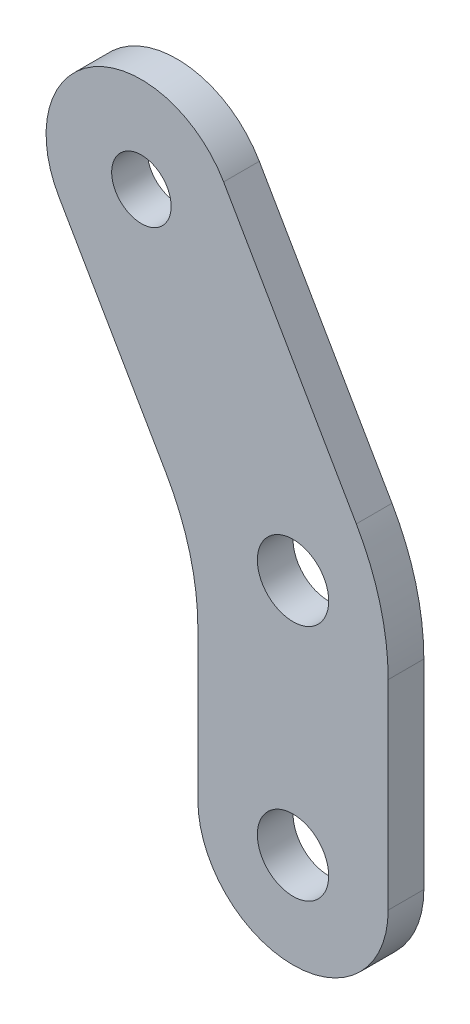
SolidWorks part; units mm, degrees
material "5052-H32"
ref_plane "Front Plane" through (0, 0, 0) normal (0, 0, 1) x (1, 0, 0)
ref_plane "Top Plane" through (0, 0, 0) normal (0, 1, 0) x (1, 0, 0)
ref_plane "Right Plane" through (0, 0, 0) normal (1, 0, 0) x (0, 0, -1)
sketch "Sketch1" plane through (0, 0, 0) normal (0, 0, 1) x (1, 0, 0)
  line L0 (-8, 0) -> (-8, 17.8564)
  line L1 (-8, 17.8564) -> (-19.6922, 38.108)
  line L2 (-19.6922, 38.108) -> (-5.8358, 46.108) construction
  line L3 (-5.8358, 46.108) -> (8, 22.1436)
  line L4 (8, 0) -> (8, 22.1436)
  line L5 (0, 0) -> (0, 20) construction
  line L6 (-8, 17.8564) -> (8, 17.8564) construction
  line L7 (0, 20) -> (-12.764, 42.108) construction
  circle A0 centre (0, 0) radius 3
  arc A1 (-8, 0) -> (8, 0) centre (0, 0) ccw
  arc A2 (-5.8358, 46.108) -> (-19.6922, 38.108) centre (-12.764, 42.108) ccw
  circle A4 centre (0, 20) radius 3
  circle A5 centre (0, 0) radius 44 construction
  circle A6 centre (-12.7498, 42.1123) radius 2.5
  point P16 (-12.5, 41.6506)
  point P17 (-11.7565, 40.3628)
  point P18 (0, 0)
  point P19 (-11.4082, 39.7597)
  point P20 (0, 0)
  dimension "D1" = 6
  dimension "D2" = 8
  dimension "D3" = 16
  dimension "D5" = 20
  dimension "D7" = 6
  dimension "D11" = 88
  dimension "D8" = 5
  dimension "D4" = 30
  dimension "D6" = 30
extrude "Boss-Extrude1" add sketch "Sketch1" along normal blind 3
fillet "Fillet1" radius 20 2 edges at (-8, 17.8564, 1.5) (8, 22.1436, 1.5)
